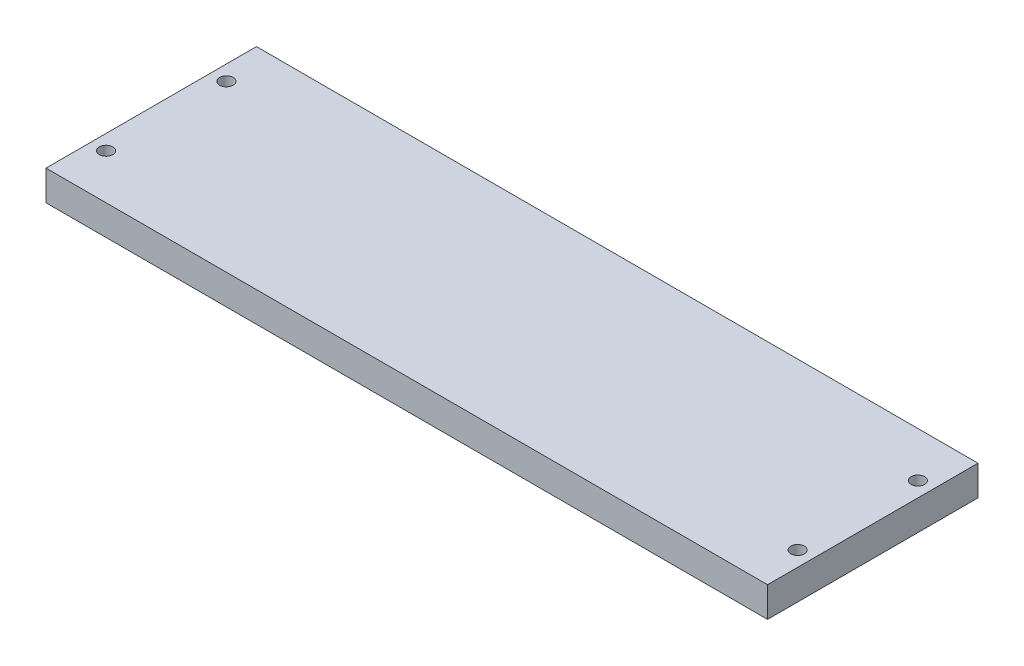
SolidWorks part; units mm, degrees
material "ABS"
ref_plane "Alzado" through (0, 0, 0) normal (0, 0, 1) x (1, 0, 0)
ref_plane "Planta" through (0, 0, 0) normal (0, 1, 0) x (1, 0, 0)
ref_plane "Vista lateral" through (0, 0, 0) normal (1, 0, 0) x (0, 0, -1)
sketch "Croquis1" plane through (0, 0, 0) normal (0, 1, 0) x (1, 0, 0)
  line L1 (-120, -35) -> (120, -35)
  line L2 (-120, -35) -> (-120, 35)
  line L3 (-120, 35) -> (120, 35)
  line L4 (120, -35) -> (120, 35)
  line L5 (-120, -35) -> (120, 35) construction
  line L6 (-120, 35) -> (120, -35) construction
  point P0 (0, 0)
  dimension "D1" = 240
  dimension "D2" = 70
extrude "Saliente-Extruir1" add sketch "Croquis1" along normal mid plane 10
sketch "Croquis2" plane through (0, 5, 0) normal (0, 1, 0) x (1, 0, 0)
  line L0 (-115, 35) -> (-115, 20) construction
  line L1 (120, 35) -> (-120, 35) construction
  line L2 (-115, 20) -> (-115, -20) construction
  line L3 (-115, -20) -> (-115, -35) construction
  line L4 (-120, -35) -> (120, -35) construction
  line L5 (-120, 35) -> (-120, -35) construction
  line L6 (0, -5.5) -> (0, 5.5) construction
  circle A0 centre (-115, 20) radius 2.25
  circle A1 centre (-115, -20) radius 2.25
  circle A2 centre (115, -20) radius 2.25
  circle A3 centre (115, 20) radius 2.25
  dimension "D3" = 4.5
  dimension "D1" = 40
  dimension "D2" = 5
extrude "Cortar-Extruir1" cut sketch "Croquis2" against normal through all
sketch "Croquis3" plane through (0, 5, 0) normal (0, 1, 0) x (1, 0, 0)
  line L0 (57.5, 0) -> (-57.5, 0) construction
  line L1 (-91, 0) -> (-24, 0) construction
  line L2 (-91, 4) -> (-24, 4)
  line L3 (-91, -4) -> (-24, -4)
  line L4 (91, 0) -> (24, 0) construction
  line L5 (91, -4) -> (24, -4)
  line L6 (91, 4) -> (24, 4)
  line L7 (0, -17.5) -> (0, 17.5) construction
  line L8 (0, 14) -> (0, 21) construction
  line L9 (-4, 14) -> (-4, 21)
  line L10 (4, 14) -> (4, 21)
  line L11 (0, -14) -> (0, -21) construction
  line L12 (4, -14) -> (4, -21)
  line L13 (-4, -14) -> (-4, -21)
  line L14 (-120, 35) -> (-120, -35) construction
  line L15 (120, 35) -> (-120, 35) construction
  arc A0 (-91, 4) -> (-91, -4) centre (-91, 0) ccw
  arc A1 (-24, -4) -> (-24, 4) centre (-24, 0) ccw
  arc A2 (91, -4) -> (91, 4) centre (91, 0) ccw
  arc A3 (24, 4) -> (24, -4) centre (24, 0) ccw
  arc A4 (-4, 14) -> (4, 14) centre (0, 14) ccw
  arc A5 (4, 21) -> (-4, 21) centre (0, 21) ccw
  arc A6 (4, -14) -> (-4, -14) centre (0, -14) ccw
  arc A7 (-4, -21) -> (4, -21) centre (0, -21) ccw
  point P3 (0, 10)
  point P4 (0, 0)
  point P7 (-57.5, 0)
  point P13 (57.5, 0)
  point P22 (0, 0)
  point P24 (0, 17.5)
  point P30 (0, -17.5)
  point P37 (-20, 0)
  point P39 (0, 25)
  point P42 (-95, 0)
  dimension "D1" = 10
  dimension "D2" = 20
  dimension "D3" = 8
  dimension "D4" = 25
  dimension "D5" = 8
  dimension "D6" = 10
extrude "Cortar-Extruir2" [suppressed] cut sketch "Croquis3" against normal through all
sketch "Croquis4" [suppressed] plane through (0, 5, 0) normal (0, 1, 0) x (1, 0, 0)
  line L0 (4, 17.5) -> (57.5, 17.5) construction
  line L2 (4, 14) -> (4, 21) construction
  line L4 (57.5, 17.5) -> (57.5, 4) construction
  line L9 (91, 4) -> (24, 4) construction
  line L10 (57.5, 14) -> (57.5, 21) construction
  line L11 (53.5, 14) -> (53.5, 21)
  line L12 (61.5, 14) -> (61.5, 21)
  line L13 (0, 25) -> (57.5, 25) construction
  line L14 (-5.5, 0) -> (5.5, 0) construction
  line L15 (57.5, -14) -> (57.5, -21) construction
  line L16 (53.5, -14) -> (53.5, -21)
  line L17 (61.5, -14) -> (61.5, -21)
  line L18 (0, -5.5) -> (0, 5.5) construction
  line L19 (-57.5, 14) -> (-57.5, 21) construction
  line L20 (-53.5, 14) -> (-53.5, 21)
  line L21 (-61.5, 14) -> (-61.5, 21)
  line L22 (-57.5, -14) -> (-57.5, -21) construction
  line L23 (-53.5, -14) -> (-53.5, -21)
  line L24 (-61.5, -14) -> (-61.5, -21)
  arc A2 (53.5, 14) -> (61.5, 14) centre (57.5, 14) ccw
  arc A3 (61.5, 21) -> (53.5, 21) centre (57.5, 21) ccw
  arc A4 (4, 21) -> (-4, 21) centre (0, 21) ccw construction
  arc A5 (53.5, -14) -> (61.5, -14) centre (57.5, -14) cw
  arc A6 (61.5, -21) -> (53.5, -21) centre (57.5, -21) cw
  arc A7 (-53.5, 14) -> (-61.5, 14) centre (-57.5, 14) cw
  arc A8 (-61.5, 21) -> (-53.5, 21) centre (-57.5, 21) cw
  arc A9 (-53.5, -14) -> (-61.5, -14) centre (-57.5, -14) ccw
  arc A10 (-61.5, -21) -> (-53.5, -21) centre (-57.5, -21) ccw
  point P9 (57.5, 17.5)
  point P23 (57.5, -17.5)
  point P32 (-57.5, 17.5)
  point P39 (-57.5, -17.5)
  dimension "D1" = 8
extrude "Cortar-Extruir3" [suppressed] cut sketch "Croquis4" against normal through all
